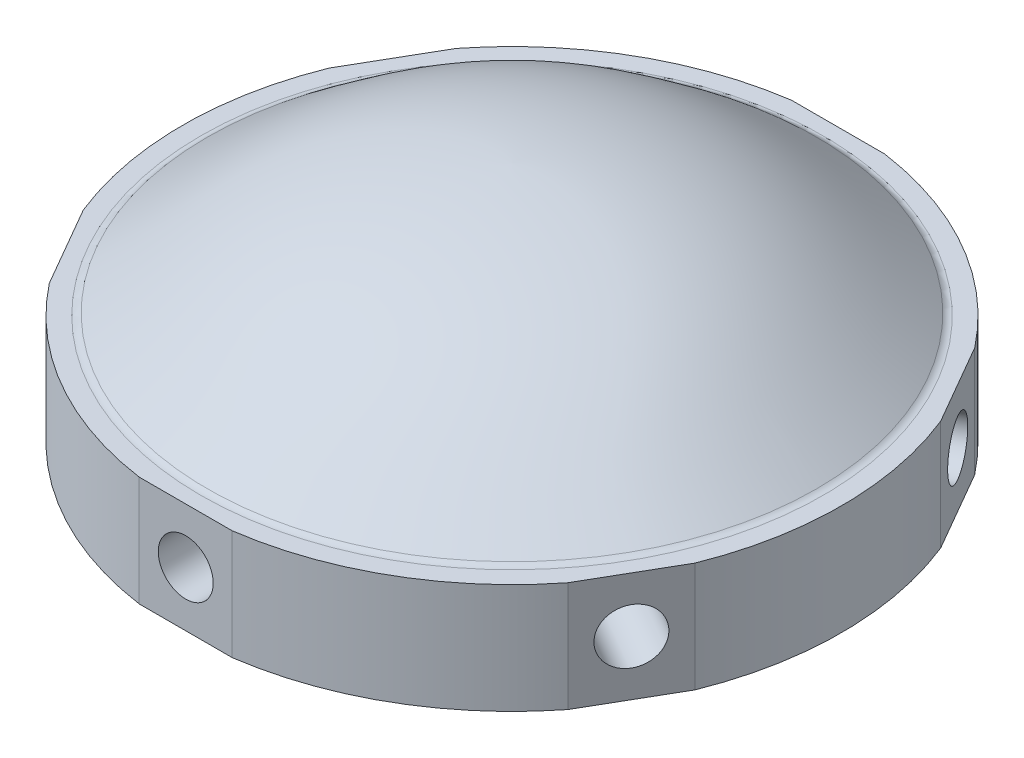
SolidWorks part; units mm, degrees
ref_plane "前视基准面" through (0, 0, 0) normal (0, 0, 1) x (1, 0, 0)
ref_plane "上视基准面" through (0, 0, 0) normal (0, 1, 0) x (1, 0, 0)
ref_plane "右视基准面" through (0, 0, 0) normal (1, 0, 0) x (0, 0, -1)
sketch "草图1" plane through (0, 0, 0) normal (0, 1, 0) x (1, 0, 0)
  line L0 (11.8025, 9.2575) -> (13.9185, 5.5925)
  line L1 (-2.116, 14.85) -> (2.116, 14.85)
  line L2 (13.9185, -5.5925) -> (11.8025, -9.2575)
  line L3 (2.116, -14.85) -> (-2.116, -14.85)
  line L4 (-11.8025, -9.2575) -> (-13.9185, -5.5925)
  line L5 (-13.9185, 5.5925) -> (-11.8025, 9.2575)
  arc A0 (-2.116, 14.85) -> (-11.8025, 9.2575) centre (0, 0) ccw
  arc A1 (-13.9185, 5.5925) -> (-13.9185, -5.5925) centre (0, 0) ccw
  arc A2 (-11.8025, -9.2575) -> (-2.116, -14.85) centre (0, 0) ccw
  arc A3 (2.116, -14.85) -> (11.8025, -9.2575) centre (0, 0) ccw
  arc A4 (13.9185, -5.5925) -> (13.9185, 5.5925) centre (0, 0) ccw
  arc A5 (11.8025, 9.2575) -> (2.116, 14.85) centre (0, 0) ccw
  point P18 (0, 0)
  dimension "D1" = 30
  dimension "D2" = 6
extrude "凸台-拉伸1" add sketch "草图1" along normal blind 5
sketch "草图2" plane through (12.8605, 0, 7.425) normal (0.866, 0, 0.5) x (0.5, 0, -0.866)
  line L0 (-2.116, 0) -> (2.116, 0) construction
  circle A0 centre (0, 2.5) radius 1.5
  dimension "D1" = 3
  dimension "D2" = 2.5
sketch "草图3" plane through (0, 0, 0) normal (0, -1, 0) x (1, 0, 0)
  circle A0 centre (0, 0) radius 5.5
  dimension "D1" = 11
extrude "凸台-拉伸2" add sketch "草图3" along normal blind 5
sketch "草图5" plane through (0, -5, 0) normal (0, -1, 0) x (1, 0, 0)
  circle A0 centre (0, 0) radius 3
  dimension "D1" = 6
sketch "草图6" plane through (0, 0, 0) normal (1, 0, 0) x (0, 0, -1)
  circle A0 centre (0, -2.5) radius 1.5
  dimension "D1" = 3
  dimension "D2" = 2.5
extrude "轴联锁孔" cut sketch "草图6" against normal up to next and the other way up to next
cosmetic thread "装饰螺纹线1" parameters "D2"=3
cosmetic thread "装饰螺纹线3" parameters "D2"=3
sketch "草图7" plane through (0, 0, 0) normal (0, 0, 1) x (1, 0, 0)
  line L0 (0, 11) -> (0, 5)
  line L1 (0, 5) -> (14, 5)
  line L2 (11.8025, 5) -> (2.116, 5) construction
  line L3 (0, 11) -> (5.5352, 10.8481) construction
  line L4 (5.5352, 10.8481) -> (8.9924, 9.0006) construction
  line L5 (8.9924, 9.0006) -> (10.4443, 7.7173) construction
  line L6 (10.4443, 7.7173) -> (14, 5) construction
  spline S0 degree 4 poles (0, 11) (5.5352, 10.8481) (8.9924, 9.0006) (10.4443, 7.7173) (14, 5) knots 0 0 0 0 0 1 1 1 1 1
revolve "旋转1" add sketch "草图7" angle 360 about L0
fillet "圆角1" radius 0.5 1 edges at (-14, 5, 0)
hole_wizard "M3 螺纹孔1" positions "3D草图1" profile "草图8" tap size "M3" standard "GB"
sketch3d "3D草图1"
  point P0 (12.8605, 2.5, 7.425)
sketch "草图8" plane through (12.8605, 2.5, 7.425) normal (0, 1, 0) x (0.5, 0, -0.866)
  line L0 (0, 0) -> (0, 8.7511)
  line L1 (0, 8.7511) -> (1.25, 8)
  line L2 (1.25, 8) -> (1.25, 0)
  line L5 (1.25, 0) -> (0, 0)
  line L10 (0, 8.7511) -> (-1.25, 8) construction
  line L11 (0, -6.35) -> (0, 107.95) construction
  dimension "螺纹孔钻头直径" = 2.5
  dimension "螺纹孔钻头深度" = 8
  dimension "导头角度" = 118
cosmetic thread "孔螺蚊线1" parameters "D1"=6, "D2"=3
pattern_circular "阵列(圆周)1" count 6 over 360 about axis through (0, 0, 0) along (0, 1, 0) of "M3 螺纹孔1"
hole_wizard "Ø6.0 (6) 直径孔1" positions "3D草图2" profile "草图9" hole size "Ø6.0" standard "GB"
sketch3d "3D草图2"
  point P0 (0, -5, 0)
sketch "草图9" plane through (0, -5, 0) normal (1, 0, 0) x (0, 0, -1)
  line L0 (0, 0) -> (0, 15.3026)
  line L1 (0, 15.3026) -> (3, 13.5)
  line L2 (3, 13.5) -> (3, 0)
  line L5 (3, 0) -> (0, 0)
  line L10 (0, 15.3026) -> (-3, 13.5) construction
  line L11 (0, -6.35) -> (0, 107.95) construction
  dimension "孔直径" = 6
  dimension "孔深度" = 13.5
  dimension "导头角度" = 118
